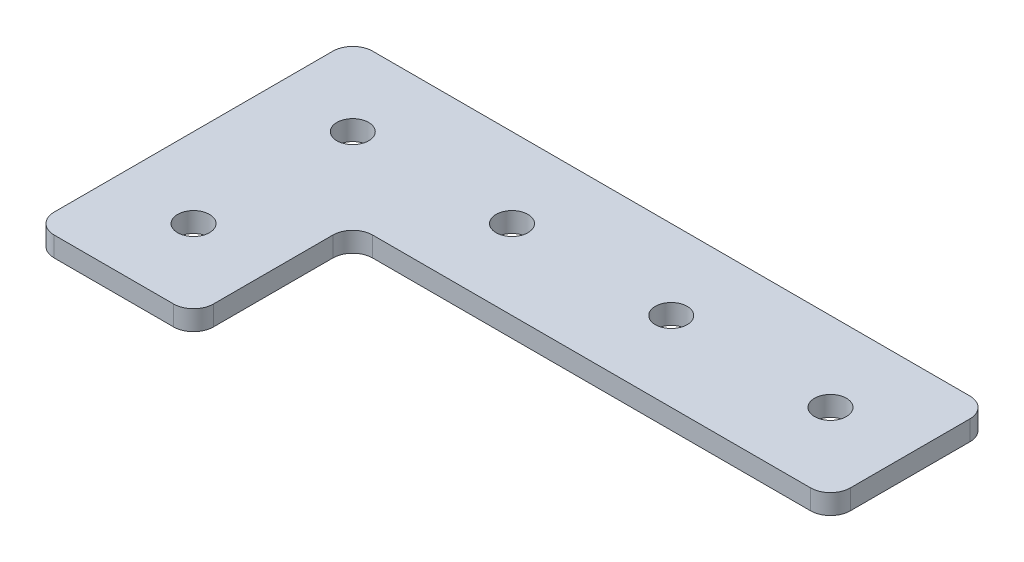
SolidWorks part; units mm, degrees
material "6061-T6 (SS)"
ref_plane "Front Plane" through (0, 0, 0) normal (0, 0, 1) x (1, 0, 0)
ref_plane "Top Plane" through (0, 0, 0) normal (0, 1, 0) x (1, 0, 0)
ref_plane "Right Plane" through (0, 0, 0) normal (1, 0, 0) x (0, 0, -1)
sketch "Sketch1" plane through (0, 0, 0) normal (0, 1, 0) x (1, 0, 0)
  line L0 (0, 0) -> (50.8, 0) construction
  line L2 (-12.7, 12.7) -> (12.7, 12.7)
  line L3 (-12.7, 12.7) -> (-12.7, -38.1)
  line L4 (-12.7, -38.1) -> (12.7, -38.1)
  line L5 (12.7, 12.7) -> (12.7, -38.1)
  line L6 (-12.7, 12.7) -> (12.7, -38.1) construction
  line L7 (-12.7, -38.1) -> (12.7, 12.7) construction
  line L8 (88.9, -12.7) -> (12.7, -12.7)
  line L9 (88.9, -12.7) -> (88.9, 12.7)
  line L10 (88.9, 12.7) -> (12.7, 12.7)
  line L11 (12.7, -12.7) -> (12.7, 12.7)
  line L12 (88.9, -12.7) -> (12.7, 12.7) construction
  line L13 (88.9, 12.7) -> (12.7, -12.7) construction
  circle A0 centre (0, -25.4) radius 2.54
  circle A1 centre (0, 0) radius 2.54
  circle A2 centre (25.4, 0) radius 2.54
  circle A3 centre (50.8, 0) radius 2.54
  circle A4 centre (76.2, 0) radius 2.54
  point P14 (0, -12.7)
  point P15 (0, 12.7)
  point P18 (50.8, 0)
  point P21 (0, 0)
  dimension "D1" = 5.08
  dimension "D2" = 25.4
  dimension "D3" = 50.8
  dimension "D4" = 25.4
  dimension "D5" = 12.7
  dimension "D6" = 50.8
  dimension "D7" = 76.2
  dimension "D8" = 25.4
extrude "Boss-Extrude1" add sketch "Sketch1" along normal blind 3.175 contours L5 L2 L3 L4 A1 A0 | L9 L10 L5 L8 A3 A2
fillet "Fillet1" radius 3.175 6 edges at (12.7, 1.5875, 38.1) (-12.7, 1.5875, 38.1) (-12.7, 1.5875, -12.7) (88.9, 1.5875, -12.7) (88.9, 1.5875, 12.7) (12.7, 1.5875, 12.7)
